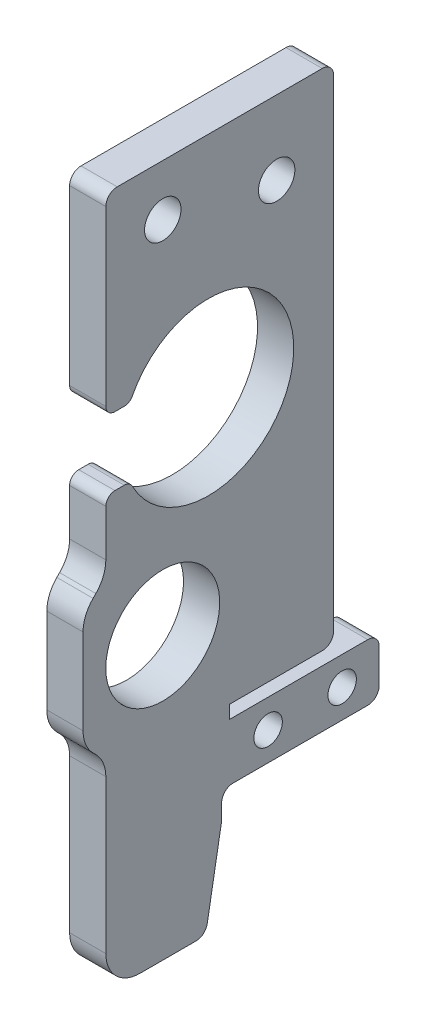
SolidWorks part; units mm, degrees
ref_plane "Front Plane" through (0, 0, 0) normal (0, 0, 1) x (1, 0, 0)
ref_plane "Top Plane" through (0, 0, 0) normal (0, 1, 0) x (1, 0, 0)
ref_plane "Right Plane" through (0, 0, 0) normal (1, 0, 0) x (0, 0, -1)
sketch "Sketch1" plane through (0, 0, 0) normal (1, 0, 0) x (0, 0, -1)
  line L0 (0, 0) -> (0, 17.7)
  line L1 (0, 17.7) -> (-2, 19.7)
  line L2 (-2, 19.7) -> (-2, 29.7)
  line L3 (-2, 29.7) -> (0, 31.7)
  line L4 (0, 31.7) -> (0, 60.81)
  line L5 (0, 60.81) -> (20, 60.81)
  line L6 (20, 60.81) -> (20, 16.53)
  line L7 (20, 16.53) -> (10.85, 16.53)
  line L8 (10.85, 16.53) -> (10.85, 15.38)
  line L9 (10.85, 15.38) -> (24, 15.38)
  line L10 (24, 15.38) -> (24, 10.38)
  line L11 (24, 10.38) -> (10.17, 10.38)
  line L12 (10.17, 10.38) -> (10.17, 0)
  line L13 (10.17, 0) -> (0, 0)
  line L14 (-8.9356, -4) -> (60.4069, -4) construction
  line L15 (5, 29.7) -> (-2, 29.7) construction
  line L16 (5, 19.7) -> (-2, 19.7) construction
  line L17 (0, 17.7) -> (0, 31.7) construction
  circle A0 centre (5, 24.7) radius 5
  circle A1 centre (5, 56.31) radius 1.6
  circle A2 centre (15, 54.31) radius 1.6
  circle A3 centre (20.75, 12.88) radius 1.25
  circle A4 centre (14.25, 12.88) radius 1.25
  point P12 (5.085, 0)
  dimension "D11" = 10
  dimension "D13" = 3.2
  dimension "D17" = 5
  dimension "D21" = 2.5
  dimension "D1" = 20
  dimension "D2" = 60.81
  dimension "D3" = 10.38
  dimension "D4" = 5
  dimension "D5" = 1.15
  dimension "D6" = 0.68
  dimension "D7" = 10.17
  dimension "D8" = 4
  dimension "D9" = 2
  dimension "D10" = 2
  dimension "D12" = 28.7
  dimension "D14" = 6.5
  dimension "D15" = 4.5
  dimension "D16" = 5
  dimension "D18" = 6.5
  dimension "D19" = 3.25
  dimension "D20" = 2.5
  dimension "D22" = 13.83
extrude "Boss-Extrude1" add sketch "Sketch1" along normal blind 3.18
chamfer "Chamfer1" distance 8 angle 10 1 edges at (1.59, 0, -10.17)
fillet "Fillet1" radius 1 7 edges at (1.59, 10.38, -10.17) (1.59, 10.38, -24) (1.59, 15.38, -24) (1.59, 16.53, -20) (1.59, 60.81, -20) (1.59, 60.81, 0) (1.59, 0, -8.7594)
fillet "Fillet2" radius 3 5 edges at (1.59, 0, 0) (1.59, 17.7, 0) (1.59, 19.7, 2) (1.59, 29.7, 2) (1.59, 31.7, 0)
sketch "Sketch3" [suppressed] plane through (0, 0, 0) normal (1, 0, 0) x (0, 0, -1)
  line L0 (0, 59.81) -> (0, 32.9426) construction
  line L1 (2.5674, 41.7448) -> (13.0251, 45.9147) construction
  line L2 (13.0251, 45.9147) -> (11.4075, 34.7732) construction
  line L3 (11.4075, 34.7732) -> (2.5674, 41.7448) construction
  circle A0 centre (9, 40.8109) radius 5
  circle A1 centre (5, 24.7) radius 5 construction
  circle A2 centre (9, 40.8109) radius 6.5 construction
  circle A3 centre (13.0251, 45.9147) radius 1.2 construction
  circle A4 centre (11.4075, 34.7732) radius 1.2 construction
  circle A5 centre (2.5674, 41.7448) radius 1.2 construction
  point P6 (0, 46.3763)
  dimension "D1" = 10
  dimension "D3" = 9
  dimension "D4" = 13
  dimension "D5" = 2.4
  dimension "D2" = 16.6
hole_wizard "CSK for M2 Flat Head Machine Screw1" [suppressed] positions "Sketch6" profile "Sketch7" countersink size "M2" standard "ANSI Metric"
sketch "Sketch6" plane through (0, 0, 0) normal (-1, 0, 0) x (0, 0, 1)
  point P0 (-13.0251, 45.9147)
  point P3 (-2.5674, 41.7448)
  point P6 (-11.4075, 34.7732)
sketch "Sketch7" plane through (0, 45.9147, -13.0251) normal (0, 1, 0) x (0, 0, 1)
  line L0 (0, 0) -> (0, 4.23)
  line L1 (0, 4.23) -> (1.2, 3.509)
  line L2 (1.2, 3.509) -> (1.2, 1)
  line L3 (1.2, 1) -> (2.2, 0)
  line L5 (2.2, 0) -> (0, 0)
  line L6 (-1.2, 1) -> (-2.2, 0) construction
  line L10 (0, 4.23) -> (-1.2, 3.509) construction
  line L11 (0, -6.35) -> (0, 107.95) construction
  dimension "Hole Dia." = 2.4
  dimension "Hole Depth" = 4.23
  dimension "Near C'Sink Dia." = 4.4
  dimension "Near C'Sink Angle" = 90
  dimension "Drill Angle" = 118
extrude "Cut-Extrude4" [suppressed] cut sketch "Sketch3" along normal through all
sketch "Sketch8" plane through (3.18, 0, 0) normal (1, 0, 0) x (0, 0, -1)
  line L0 (0, 59.81) -> (0, 32.9426) construction
  line L1 (9, 40.8109) -> (0, 40.8109) construction
  line L2 (0, 43.8109) -> (2.1261, 43.8109)
  line L3 (2.1261, 37.8109) -> (0, 37.8109)
  line L4 (0, 37.8109) -> (0, 43.8109)
  arc A0 (2.1261, 37.8109) -> (2.1261, 43.8109) centre (9, 40.8109) ccw
  circle A1 centre (5, 24.7) radius 5 construction
  point P11 (0, 40.8109)
  dimension "D1" = 16.6
  dimension "D2" = 15
  dimension "D3" = 9
  dimension "D4" = 6
extrude "Cut-Extrude5" cut sketch "Sketch8" against normal through all
fillet "Fillet3" radius 0.8 4 edges at (1.59, 43.8109, -2.1261) (1.59, 37.8109, -2.1261) (1.59, 37.8109, 0) (1.59, 43.8109, 0)
